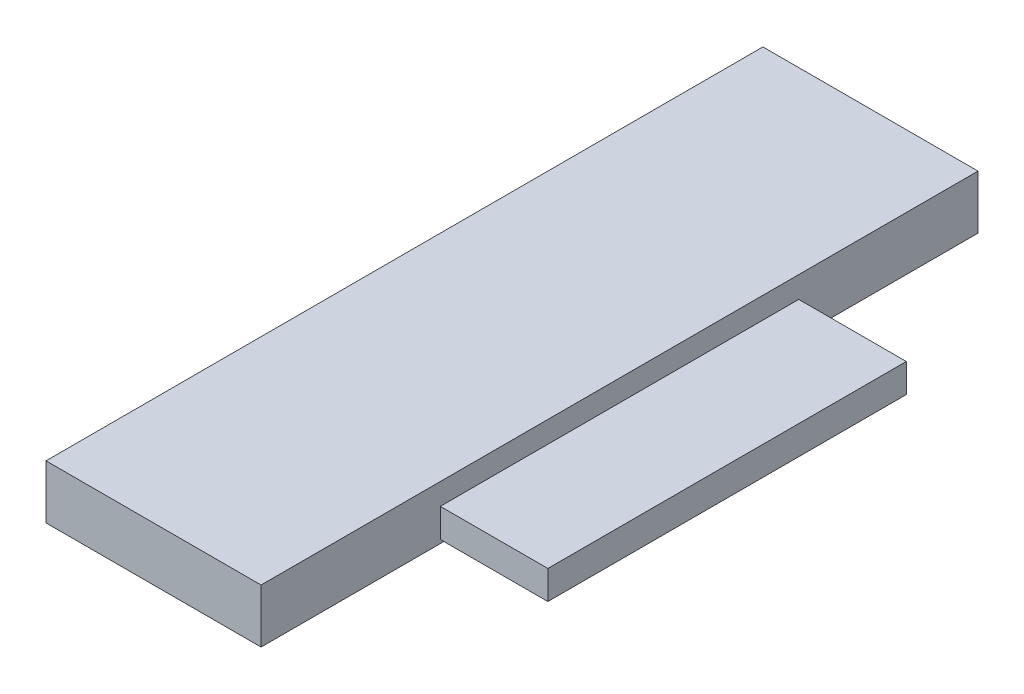
SolidWorks part; units mm, degrees
material "99.5% Aluminum Oxide (2)"
ref_plane "Front" through (0, 0, 0) normal (0, 0, 1) x (1, 0, 0)
ref_plane "Top" through (0, 0, 0) normal (0, 1, 0) x (1, 0, 0)
ref_plane "Right" through (0, 0, 0) normal (1, 0, 0) x (0, 0, -1)
sketch "Sketch1" plane through (0, 0, 0) normal (0, 1, 0) x (1, 0, 0)
  line L1 (-30, 50) -> (0, 50)
  line L2 (-30, 50) -> (-30, -50)
  line L3 (-30, -50) -> (0, -50)
  line L4 (0, 50) -> (0, -50)
  dimension "D1" = 100
  dimension "D2" = 30
extrude "Boss-Extrude1" add sketch "Sketch1" along normal mid plane 7.5
sketch "Sketch2" plane through (0, 3.75, 0) normal (0, 1, 0) x (1, 0, 0)
  line L0 (0, -50) -> (0, 50) construction
  line L1 (0, 25) -> (15, 25)
  line L2 (0, 25) -> (0, -25)
  line L3 (0, -25) -> (15, -25)
  line L4 (15, 25) -> (15, -25)
  dimension "D1" = 15
  dimension "D2" = 50
extrude "Boss-Extrude2" add sketch "Sketch2" against normal blind 4 from offset 3
equation "\"D19@Boss-Extrude2\"=\"VerticalOffset\""
equation "\"D1@Boss-Extrude2\"=\"FingerThickness\""
